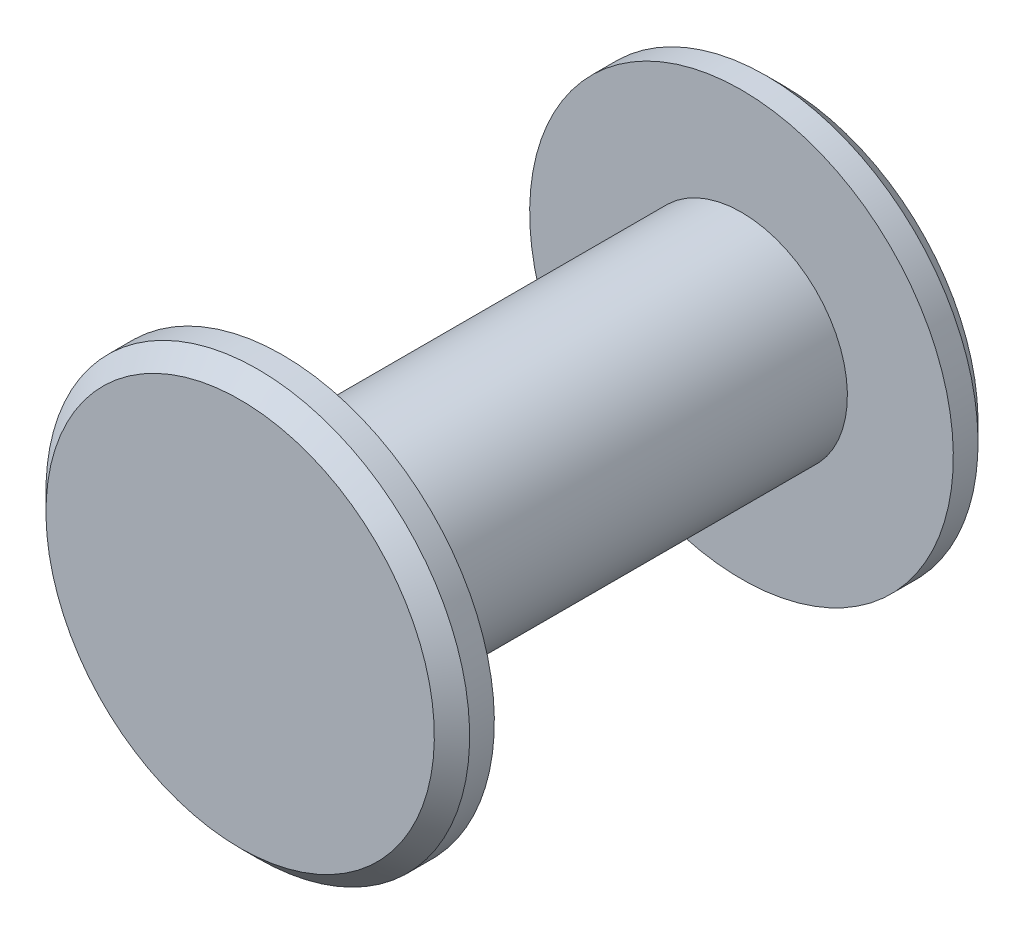
SolidWorks part; units mm, degrees
ref_plane "Front Plane" through (0, 0, 0) normal (0, 0, 1) x (1, 0, 0)
ref_plane "Top Plane" through (0, 0, 0) normal (0, 1, 0) x (1, 0, 0)
ref_plane "Right Plane" through (0, 0, 0) normal (1, 0, 0) x (0, 0, -1)
sketch "Sketch1" plane through (0, 0, 0) normal (1, 0, 0) x (0, 0, -1)
  line L0 (0, 0) -> (0, 3)
  line L1 (0, 3) -> (0.6, 3)
  line L2 (0.6, 3) -> (0.6, 1.5)
  line L3 (0.6, 1.5) -> (7.1, 1.5)
  line L4 (7.1, 1.5) -> (7.1, 3)
  line L5 (7.1, 3) -> (7.7, 3)
  line L6 (7.7, 3) -> (7.7, 0)
  line L7 (7.7, 0) -> (0, 0)
  line L8 (0, 0) -> (-7.7, 0) construction
  dimension "D1" = 6.5
  dimension "D2" = 0.6
  dimension "D3" = 3
  dimension "D4" = 6
revolve "Revolve1" add sketch "Sketch1" angle 360 about L8
chamfer "Chamfer1" distance 0.25 angle 45 2 edges at (0, 3, -7.7) (0, 3, 0)
equation "\"a\"= 1"
equation "\"b\"= 1"
equation "\"c\"= 1"
equation "\"d\"= 1"
equation "\"e\"= 1"
equation "\"x\"= 1"
equation "\"y\"= 1"
equation "\"z\"= 1"
